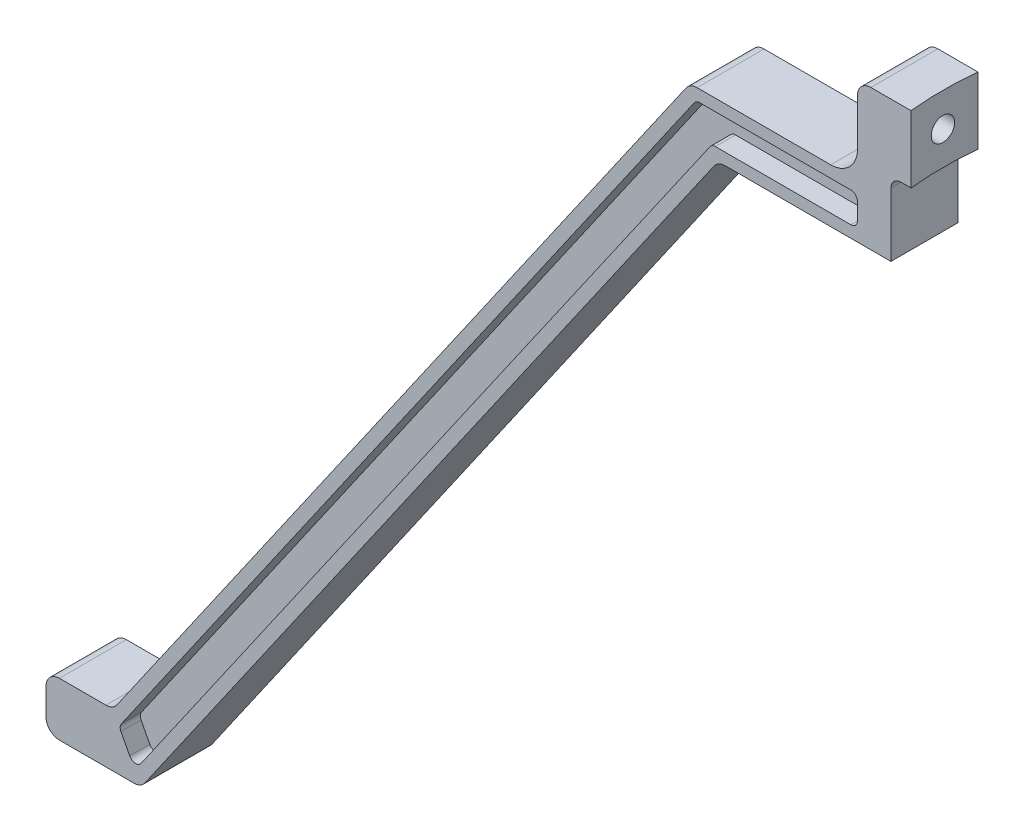
SolidWorks part; units mm, degrees
ref_plane "Front Plane" through (0, 0, 0) normal (0, 0, 1) x (1, 0, 0)
ref_plane "Top Plane" through (0, 0, 0) normal (0, 1, 0) x (1, 0, 0)
ref_plane "Right Plane" through (0, 0, 0) normal (1, 0, 0) x (0, 0, -1)
sketch "Sketch1" plane through (0, 0, 0) normal (0, 1, 0) x (1, 0, 0)
  line L0 (0, 0) -> (50000, 0) construction
  line L1 (-47.2361, 5) -> (-55.2361, 5)
  line L2 (-55.2361, 5) -> (-55.2361, -5)
  line L3 (-47.2361, -5) -> (-55.2361, -5)
  circle A0 centre (0, 0) radius 47.5 construction
  arc A1 (-47.2361, 5) -> (-47.2361, -5) centre (0, 0) ccw
  point P10 (-55.2361, 0)
  dimension "D1" = 95
  dimension "D2" = 10
  dimension "D3" = 8
extrude "Boss-Extrude1" add sketch "Sketch1" against normal blind 10
sketch "Sketch2" plane through (-55.2361, 0, 0) normal (-1, 0, 0) x (0, 0, 1)
  line L0 (0, 0) -> (0, -10) construction
  line L1 (-5, -10) -> (5, -10) construction
  line L2 (-5, -5) -> (5, -5) construction
  line L3 (-5, -10) -> (-5, 0) construction
  line L4 (5, -10) -> (5, 0) construction
  circle A0 centre (0, -5) radius 1.75
  dimension "D1" = 3.5
extrude "Cut-Extrude1" cut sketch "Sketch2" against normal blind 10
ref_plane "Plane1" through (0, 0, 0) normal (0, 0, 1) x (1, 0, 0)
sketch "Sketch3" plane through (0, 0, 0) normal (0, 0, 1) x (1, 0, 0)
  line L1 (-80.2361, -13) -> (-166.4184, -137)
  line L2 (-166.4184, -137) -> (-176.4184, -137)
  line L3 (-176.4184, -137) -> (-176.4184, -145)
  line L4 (-176.4184, -145) -> (-162.2361, -145)
  line L5 (-162.2361, -145) -> (-76.0538, -21)
  line L10 (-55.2361, -10) -> (-55.2361, -13)
  line L11 (-55.2361, -13) -> (-80.2361, -13)
  line L12 (-76.0538, -21) -> (-50.2361, -21)
  line L14 (-55.2361, -10) -> (-47.2361, -10) construction
  line L15 (-50.2361, -10) -> (-55.2361, -10)
  line L16 (-50.2361, -10) -> (-50.2361, -21)
  line L17 (-47.2361, -10) -> (-47.2361, 0) construction
  dimension "D1" = 8
  dimension "D2" = 8
  dimension "D3" = 3
  dimension "D4" = 25
  dimension "D5" = 8
  dimension "D6" = 10
  dimension "D7" = 115
  dimension "D8" = 135
  dimension "D9" = 3
extrude "Boss-Extrude2" add sketch "Sketch3" along normal mid plane 10
sketch "Sketch4" plane through (0, 0, 5) normal (0, 0, 1) x (1, 0, 0)
  line L0 (-166.4184, -137) -> (-162.2361, -145) construction
  line L1 (-80.2361, -13) -> (-76.0538, -21) construction
  line L2 (-55.2361, -13) -> (-55.2361, -21) construction
  line L3 (-76.0538, -21) -> (-50.2361, -21) construction
  line L4 (-55.2361, -17) -> (-78.145, -17) construction
  line L5 (-78.145, -17) -> (-164.3273, -141) construction
  line L6 (-164.3273, -141) -> (-165.5035, -138.75)
  line L7 (-165.5035, -138.75) -> (-79.3212, -14.75)
  line L8 (-79.3212, -14.75) -> (-55.2361, -14.75)
  line L9 (-55.2361, -19.25) -> (-76.9687, -19.25)
  line L10 (-76.9687, -19.25) -> (-163.151, -143.25)
  line L11 (-164.3273, -141) -> (-163.151, -143.25)
  line L12 (-55.2361, -14.75) -> (-55.2361, -19.25)
  dimension "D1" = 2.25
  dimension "D2" = 2.25
extrude "Cut-Extrude2" cut sketch "Sketch4" against normal blind 3
mirror "Mirror1" about plane through (0, 0, 0) normal (0, 0, 1) of "Cut-Extrude2"
fillet "Fillet1" radius 4 1 edges at (-55.2361, -13, 0)
fillet "Fillet2" radius 1.5 1 edges at (-50.2361, -10, 0)
fillet "Fillet3" radius 2 7 edges at (-55.2361, 0, 0) (-176.4184, -145, 0) (-176.4184, -137, 0) (-166.4184, -137, 0) (-162.2361, -145, 0) (-80.2361, -13, 0) (-76.0538, -21, 0)
fillet "Fillet4" radius 1 12 edges at (-163.151, -143.25, -3.5) (-76.9687, -19.25, -3.5) (-79.3212, -14.75, -3.5) (-165.5035, -138.75, -3.5) (-55.2361, -19.25, -3.5) (-55.2361, -14.75, -3.5) (-163.151, -143.25, 3.5) (-165.5035, -138.75, 3.5) (-76.9687, -19.25, 3.5) (-79.3212, -14.75, 3.5) (-55.2361, -19.25, 3.5) (-55.2361, -14.75, 3.5)
